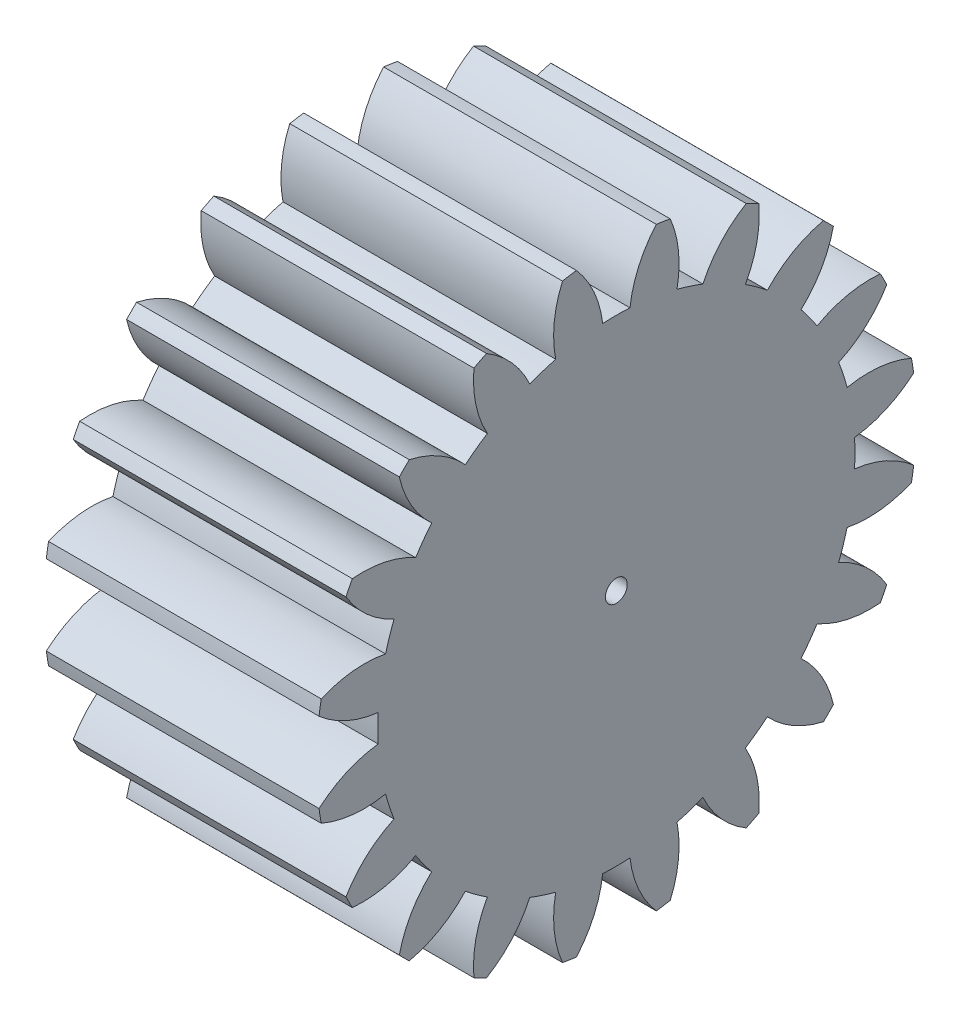
SolidWorks part; units mm, degrees
ref_plane "Plane1" through (0, 0, 0) normal (0, 0, 1) x (1, 0, 0)
ref_plane "Plane2" through (0, 0, 0) normal (0, 1, 0) x (1, 0, 0)
ref_plane "Plane3" through (0, 0, 0) normal (1, 0, 0) x (0, 0, -1)
sketch "HoldingSke" plane through (0, 0, 0) normal (0, 1, 0) x (1, 0, 0)
  line L0 (0, 0) -> (0.9397, -0.342)
  line L1 (-15, 0) -> (100, 0) construction
  line L2 (0, 0) -> (-2.1039, 2.3779)
  line L3 (0, 0) -> (-11.863, 4.5341)
  line L4 (0, 0) -> (8.1152, 2.9537)
  line L5 (0, 0) -> (-46.8476, -17.4728)
  line L6 (0, 0) -> (-4.9738, -3.3558)
  line L7 (-2.1039, 2.3779) -> (8.6586, 51.2059)
  line L8 (-76.2, 54.61) -> (-76.1, 54.61)
  line L9 (-71.009, 38.7566) -> (-53.1078, 45.2721)
  line L10 (-76.2, 71.12) -> (104.1128, 71.12)
  line L11 (0, 0) -> (-6, 0)
  line L12 (-76.2, 101.6) -> (-76.162, 101.6)
  line L13 (24.9733, 27.94) -> (52.9518, 28.4284)
  line L14 (24.9733, 27.94) -> (24.9743, 27.94)
  line L15 (24.9733, 27.94) -> (100.4006, 29.5858)
  line L16 (-63.627, -1) -> (-12.827, -1)
  circle A0 centre (0, 0) radius 0.4
  circle A1 centre (0, 0) radius 8.749
  circle A2 centre (0, 0) radius 37.5
  circle A3 centre (0, 0) radius 0.4
  dimension "MHD" = 17.498
  dimension "Hub_dia" = 75
  dimension "Bore" = 0.8
  dimension "MBD" = 0.8
  dimension "Num_teeth" = 20
  dimension "Pitch" = 1
  dimension "Overall_len" = 50
  dimension "Show_teeth" = 20
  dimension "Thickness" = 6
  dimension "OAL" = 50.0001
  dimension "T_dim" = 0.1
  dimension "Ap" = 20
  dimension "H" = 19.05
  dimension "Pitch_radius" = 180.3128
  dimension "Width" = 6
  dimension "Backlash" = 0.038
  dimension "Addendum_fac" = 1
  dimension "Dedendum_fac" = 1.25
  dimension "Clearance_fac" = 0.25
  dimension "Dedendum_add" = 0.001
  dimension "Module" = 1
sketch "BasProSke" plane through (0, 0, 0) normal (0, 1, 0) x (1, 0, 0)
  line L0 (-10, 0) -> (60, 0) construction
  line L1 (0, 0) -> (0, 11)
  line L2 (0, 0) -> (10, 0)
  line L3 (10, 0) -> (10, 11)
  line L4 (10, 11) -> (0, 11)
  dimension "Thickness" = 10
  dimension "Diameter" = 22
revolve "Base-Revolve" add sketch "BasProSke" angle 360 about L0
sketch "TooCutSke" plane through (0, 0, 0) normal (1, 0, 0) x (0, 0, -1)
  line L1 (0, 0) -> (0, 107) construction
  line L2 (0, 0) -> (-0.8511, 9.9637) construction
  line L3 (0, 0) -> (-3.1206, 19.7028) construction
  line L4 (-0.8511, 9.9637) -> (-1.5603, 9.8514) construction
  arc A0 (0.4999, 8.7347) -> (-0.4999, 8.7347) centre (0, 0) ccw
  arc A1 (1.4852, 10.9249) -> (-1.4852, 10.9249) centre (0, 0) ccw
  circle A2 centre (0, 0) radius 10 construction
  circle A3 centre (0, 0) radius 9.3969 construction
  arc A4 (-0.4999, 8.7347) -> (-1.4852, 10.9249) centre (-4.4722, 8.2645) ccw
  arc A5 (1.4852, 10.9249) -> (0.4999, 8.7347) centre (4.4722, 8.2645) ccw
  dimension "Root_dia" = 17.498
  dimension "Overcut_dia" = 22.0508
  dimension "Pitch_dia" = 20
  dimension "Base_dia" = 18.7939
  dimension "Flank_rad" = 4
  dimension "Half_ang" = 9
  dimension "Half_CT" = 0.7181
extrude "ToothCut" cut sketch "TooCutSke" along normal through all
fillet "Breaks" [suppressed] radius 0.02
fillet "RootFillets" [suppressed] radius 0.251
pattern_circular "TeethCuts" count 20 over 360 about axis through (0, 0, 0) along (1, 0, 0) of "ToothCut", "RootFillets", "Breaks"
sketch "HubNeaOneSke" plane through (0, 0, 0) normal (-1, 0, 0) x (0, 0, 1)
  circle A0 centre (0, 0) radius 8.749
  dimension "Diameter" = 17.498
extrude "HubNearOne" [suppressed] add sketch "HubNeaOneSke" along normal blind 40.0001
sketch "HubNeaBotSke" plane through (0, 0, 0) normal (-1, 0, 0) x (0, 0, 1)
  circle A0 centre (0, 0) radius 8.749
  dimension "Diameter" = 17.498
extrude "HubNearBoth" [suppressed] add sketch "HubNeaBotSke" along normal blind 20
ref_plane "FarPln" through (10, 0, 0) normal (1, 0, 0) x (0, 0, -1)
sketch "HubFarSke" plane through (10, 0, 0) normal (1, 0, 0) x (0, 0, -1)
  circle A0 centre (0, 0) radius 8.749
  dimension "Diameter" = 17.498
extrude "HubFar" [suppressed] add sketch "HubFarSke" along normal blind 20
sketch "BorSke" plane through (0, 0, 0) normal (1, 0, 0) x (0, 0, -1)
  circle A0 centre (0, 0) radius 0.4
  dimension "Diameter" = 0.8
extrude "Bore" cut sketch "BorSke" along normal mid plane 100.0001
sketch "KeySke" plane through (0, 0, 0) normal (1, 0, 0) x (0, 0, -1)
  line L0 (-0.05, 0) -> (-0.05, 0.5)
  line L1 (-0.05, 0.5) -> (0.05, 0.5)
  line L2 (0.05, 0.5) -> (0.05, 0)
  line L3 (0, 0) -> (0, 34) construction
  line L4 (-0.05, 0) -> (0.05, 0)
  dimension "Offset" = 0.5
  dimension "Width" = 0.1
extrude "Keyway" [suppressed] cut sketch "KeySke" along normal mid plane 100.0001
pattern_circular "Keyway2" [suppressed] count 2 every 90 about axis through (-10, 0, 0) along (1, 0, 0)
equation "' \"Module@HoldingSke\" = 6.35"
equation "' \"Num_teeth@HoldingSke\" = 12"
equation "' \"Ap@HoldingSke\" =  20"
equation "' \"Ap@HoldingSke\" = 20"
equation "' \"Width@HoldingSke\" = 0.5 * 25.4"
equation "' \"Hub_dia@HoldingSke\"= 1 * 25.4"
equation "' \"Hub_dia@HoldingSke\" = 1 * 25.4"
equation "' \"Overall_len@HoldingSke\" = 1.0 * 25.4"
equation "' \"Bore@HoldingSke\" = 0.75 * 25.4"
equation "' \"T_dim@HoldingSke\" = 0.1 * 25.4"
equation "' \"Width@KeySke\" = 0.25 * 25.4"
equation "' \"Show_teeth@HoldingSke\" = 13"
equation "' \"Backlash@HoldingSke\" = 0.009 * 25.4"
equation "' \"Addendum_fac@HoldingSke\" = 1.0"
equation "' \"Dedendum_fac@HoldingSke\" = 1.25"
equation "' \"Dedendum_add@HoldingSke\" = 0.00005 * 25.4"
equation "' \"Clearance_fac@HoldingSke\" = 0.25"
equation "\"Pitch@HoldingSke\" = 1 / \"Module@HoldingSke\""
equation "\"Overcut_dia@TooCutSke\" = (\"Num_teeth@HoldingSke\" + 2 * \"Addendum_fac@HoldingSke\") / \"Pitch@HoldingSke\" + 0.002 * 25.4"
equation "\"Pitch_dia@TooCutSke\" = \"Num_teeth@HoldingSke\" / \"Pitch@HoldingSke\""
equation "\"Base_dia@TooCutSke\" = \"Num_teeth@HoldingSke\" / \"Pitch@HoldingSke\" * cos((\"Ap@HoldingSke\"  * 3.14159265 / 180))"
equation "\"Root_dia@TooCutSke\" = (\"Num_teeth@HoldingSke\" + 2) / \"Pitch@HoldingSke\" - 2 * (\"Addendum_fac@HoldingSke\" + \"Dedendum_fac@HoldingSke\") / \"Pitch@HoldingSke\" - \"Dedendum_add@HoldingSke\" * 2"
equation "\"Half_ang@TooCutSke\" = 180 / \"Num_teeth@HoldingSke\""
equation "\"Half_CT@TooCutSke\" = \"Num_teeth@HoldingSke\" / \"Pitch@HoldingSke\" * sin((3.14159265 / 2 / \"Num_teeth@HoldingSke\")) / 2 - 7 * \"Backlash@HoldingSke\" / 4"
equation "\"Flank_rad@TooCutSke\" = \"Num_teeth@HoldingSke\" / \"Pitch@HoldingSke\" / 5"
equation "\"Radius@RootFillets\" = \"Clearance_fac@HoldingSke\" / \"Pitch@HoldingSke\" + \"Dedendum_add@HoldingSke\""
equation "\"Break_rad@Breaks\" = 0.02 / \"Pitch@HoldingSke\""
equation "\"Thickness@HoldingSke\" = \"Width@HoldingSke\""
equation "\"OAL@HoldingSke\" = \"Thickness@HoldingSke\""
equation "\"MHD@HoldingSke\" = (\"Num_teeth@HoldingSke\" + 2) / \"Pitch@HoldingSke\" - 2 * (\"Addendum_fac@HoldingSke\" + \"Dedendum_fac@HoldingSke\")  / \"Pitch@HoldingSke\" - \"Dedendum_add@HoldingSke\" * 2"
equation "\"MBD@HoldingSke\" = (\"Num_teeth@HoldingSke\" + 2) / \"Pitch@HoldingSke\" - 2 * (\"Addendum_fac@HoldingSke\" + \"Dedendum_fac@HoldingSke\")  / \"Pitch@HoldingSke\" - \"Dedendum_add@HoldingSke\" * 2 - 0.002 * 25.4"
equation "\"MHD@HoldingSke\" = ((sgn( \"MHD@HoldingSke\" - \"Hub_dia@HoldingSke\" )-1)*( \"MHD@HoldingSke\" - \"Hub_dia@HoldingSke\" ))/-2+ \"Hub_dia@HoldingSke\""
equation "\"MBD@HoldingSke\" = ((sgn( \"MBD@HoldingSke\" - \"Bore@HoldingSke\" )-1)*( \"MBD@HoldingSke\" - \"Bore@HoldingSke\" ))/-2+ \"Bore@HoldingSke\""
equation "\"OAL@HoldingSke\" = ((sgn( \"OAL@HoldingSke\" - \"Overall_len@HoldingSke\" )+1)*( \"OAL@HoldingSke\" - \"Overall_len@HoldingSke\" ))/2 + \"Overall_len@HoldingSke\" + 0.000002 * 25.4"
equation "\"Num_teeth@TeethCuts\" = int( \"Show_teeth@HoldingSke\" ) + 1"
equation "\"Num_teeth@TeethCuts\" = ((sgn( \"Num_teeth@TeethCuts\" - \"Num_teeth@HoldingSke\" )-1)*( \"Num_teeth@TeethCuts\" - \"Num_teeth@HoldingSke\" ))/-2+ \"Num_teeth@HoldingSke\""
equation "\"Num_teeth@TeethCuts\" = ((sgn( \"Num_teeth@TeethCuts\" - 2.0)+1)*( \"Num_teeth@TeethCuts\" - 2.0))/2 +2.0"
equation "\"Angle@TeethCuts\" = 360.0 / \"Num_teeth@HoldingSke\""
equation "\"Diameter@BasProSke\" = (\"Num_teeth@HoldingSke\" + 2 * \"Addendum_fac@HoldingSke\") / \"Pitch@HoldingSke\""
equation "' \"Fillet_rad@BasProSke\" =  \"Thickness@HoldingSke\" * 0.05"
equation "' \"Fillet_rad@BasProSke\" = \"Thickness@HoldingSke\" * 0.05"
equation "\"MHD@HoldingSke\" = ((sgn( \"MHD@HoldingSke\" - \"Root_dia@TooCutSke\" )-1)*( \"MHD@HoldingSke\" - \"Root_dia@TooCutSke\" ))/-2+ \"Root_dia@TooCutSke\""
equation "\"Diameter@HubNeaOneSke\" = \"MHD@HoldingSke\""
equation "\"Length@HubNearOne\" = \"OAL@HoldingSke\" - \"Thickness@BasProSke\""
equation "\"Diameter@HubNeaBotSke\" = \"MHD@HoldingSke\""
equation "\"Length@HubNearBoth\" = ( \"OAL@HoldingSke\" - \"Thickness@BasProSke\" ) / 2.0"
equation "\"Thickness@FarPln\" = \"Thickness@BasProSke\""
equation "\"Diameter@HubFarSke\" = \"MHD@HoldingSke\""
equation "\"Length@HubFar\" = ( \"OAL@HoldingSke\" - \"Thickness@BasProSke\" ) / 2.0"
equation "\"Diameter@BorSke\" = \"MBD@HoldingSke\""
equation "\"D1@Bore\" = \"OAL@HoldingSke\" * 2.0"
equation "\"D1@Keyway\" = \"OAL@HoldingSke\" * 2.0"
equation "\"Offset@KeySke\" = \"T_dim@HoldingSke\" + \"MBD@HoldingSke\" / 2.0"
